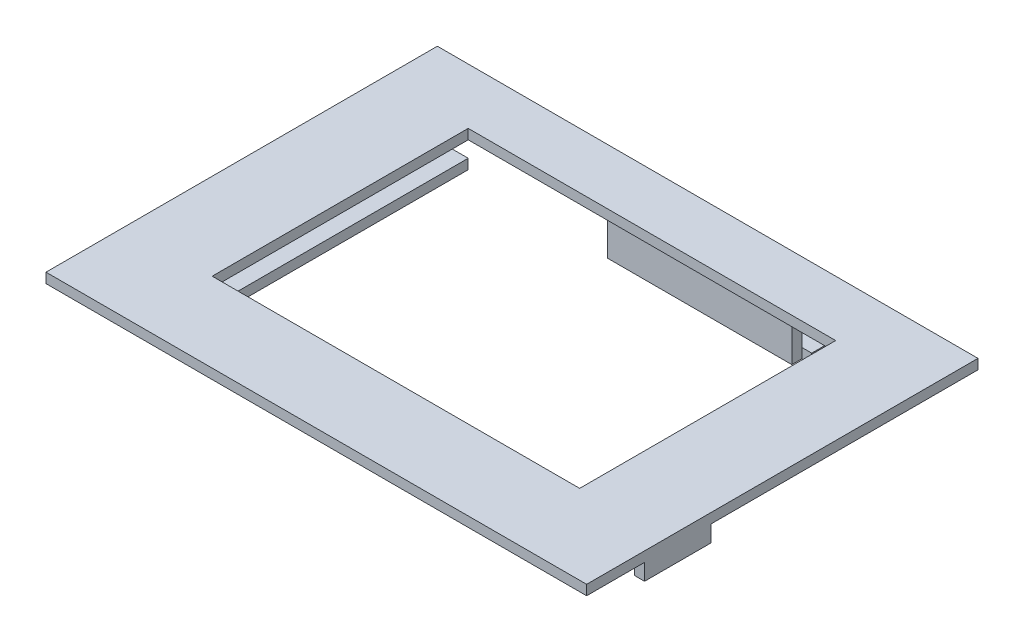
SolidWorks part; units mm, degrees
ref_plane "Front Plane" through (0, 0, 0) normal (0, 0, 1) x (1, 0, 0)
ref_plane "Top Plane" through (0, 0, 0) normal (0, 1, 0) x (1, 0, 0)
ref_plane "Right Plane" through (0, 0, 0) normal (1, 0, 0) x (0, 0, -1)
sketch "Sketch1" plane through (0, 0, 0) normal (0, 1, 0) x (1, 0, 0)
  line L1 (-33.7969, 23.441) -> (20.5331, 23.441)
  line L2 (-33.7969, 23.441) -> (-33.7969, -15.889)
  line L3 (-33.7969, -15.889) -> (20.5331, -15.889)
  line L4 (20.5331, 23.441) -> (20.5331, -15.889)
  dimension "D1" = 39.33
  dimension "D2" = 54.33
extrude "Boss-Extrude1" add sketch "Sketch1" along normal blind 1
sketch "Sketch2" plane through (20.5331, 0, 0) normal (1, 0, 0) x (0, 0, -1)
  line L0 (-15.889, 1) -> (-15.889, 4.0157) construction
  line L1 (-15.889, 4.0157) -> (-10.069, 4.0157) construction
  line L2 (-10.069, 4.0157) -> (-3.369, 4.0157) construction
  line L3 (-15.889, 0) -> (23.441, 0) construction
  line L4 (-10.069, 0) -> (-3.369, 0)
  line L5 (-10.069, 0) -> (-10.069, -1.65)
  line L6 (-10.069, -1.65) -> (-3.369, -1.65)
  line L7 (-3.369, 0) -> (-3.369, -1.65)
  dimension "D1" = 5.82
  dimension "D2" = 6.7
  dimension "D3" = 1.65
extrude "Boss-Extrude2" add sketch "Sketch2" against normal blind 1
sketch "Sketch3" plane through (0, 0, 15.889) normal (0, 0, 1) x (1, 0, 0)
  line L0 (20.5331, 1) -> (20.5331, 7.8741) construction
  line L1 (20.5331, 7.8741) -> (3.8231, 7.8741) construction
  line L2 (-33.7969, 1) -> (-33.7969, 7.8741) construction
  line L3 (-33.7969, 7.8741) -> (-16.6869, 7.8741) construction
  line L4 (-33.7969, 0) -> (20.5331, 0) construction
  line L5 (-16.6869, 0) -> (3.8231, 0)
  line L6 (-16.6869, 0) -> (-16.6869, -4.6)
  line L7 (-16.6869, -4.6) -> (3.8231, -4.6)
  line L8 (3.8231, 0) -> (3.8231, -4.6)
  dimension "D1" = 16.71
  dimension "D2" = 17.11
  dimension "D3" = 4.6
extrude "Boss-Extrude3" add sketch "Sketch3" against normal blind 1
sketch "Sketch5" plane through (0, 1, 0) normal (0, 1, 0) x (1, 0, 0)
  line L0 (-33.7969, 23.441) -> (-31.6756, 21.3197) construction
  line L1 (20.5331, -15.889) -> (18.4118, -13.7677) construction
  line L3 (-31.6756, 21.3197) -> (18.4118, 21.3197)
  line L4 (-31.6756, 21.3197) -> (-31.6756, -13.7677)
  line L5 (-31.6756, -13.7677) -> (18.4118, -13.7677)
  line L6 (18.4118, 21.3197) -> (18.4118, -13.7677)
  dimension "D1" = 3
  dimension "D2" = 3
extrude "Cut-Extrude1" cut sketch "Sketch5" against normal blind 11
sketch "Sketch6" plane through (0, 0, -23.441) normal (0, 0, -1) x (-1, 0, 0)
  line L0 (-20.5331, 1) -> (-20.5331, 5.1933) construction
  line L1 (-20.5331, 5.1933) -> (-2.8231, 5.1933) construction
  line L2 (-2.8231, 5.1933) -> (15.6769, 5.1933) construction
  line L3 (-3.8231, 0) -> (16.6869, 0) construction
  line L4 (-2.8231, 0) -> (15.6769, 0)
  line L5 (-2.8231, 0) -> (-2.8231, -7.9)
  line L6 (-2.8231, -7.9) -> (15.6769, -7.9)
  line L7 (15.6769, 0) -> (15.6769, -7.9)
  dimension "D1" = 17.71
  dimension "D2" = 18.5
  dimension "D3" = 7.9
extrude "Boss-Extrude5" add sketch "Sketch6" against normal blind 1
sketch "Sketch7" plane through (0, -4.6, 0) normal (0, -1, 0) x (1, 0, 0)
  line L1 (-16.6869, 14.889) -> (3.8231, 14.889)
  line L2 (-16.6869, 14.889) -> (-16.6869, 15.889)
  line L3 (-16.6869, 15.889) -> (3.8231, 15.889)
  line L4 (3.8231, 14.889) -> (3.8231, 15.889)
extrude "Cut-Extrude3" cut sketch "Sketch7" against normal blind 4.6
sketch "Sketch10" plane through (-33.7969, 0, 0) normal (-1, 0, 0) x (0, 0, 1)
  line L0 (-23.441, 1) -> (15.889, 1) construction
  line L1 (15.889, 0) -> (7.889, 0)
  line L2 (15.889, 0) -> (15.889, 1)
  line L3 (15.889, 1) -> (7.889, 1)
  line L4 (7.889, 0) -> (7.889, 1)
  line L6 (-23.441, 0) -> (15.889, 0) construction
  line L7 (-23.441, 1) -> (-17.841, 1)
  line L8 (-23.441, 1) -> (-23.441, 0)
  line L9 (-23.441, 0) -> (-17.841, 0)
  line L10 (-17.841, 1) -> (-17.841, 0)
  point P14 (0, 0)
  dimension "D1" = 8
  dimension "D2" = 5.6
extrude "Boss-Extrude8" add sketch "Sketch10" against normal up to vertex (54.33 mm away)
sketch "Sketch11" plane through (0, 0, 15.889) normal (0, 0, 1) x (1, 0, 0)
  line L0 (-33.7969, 1) -> (20.5331, 1) construction
  line L1 (20.5331, 0) -> (11.8331, 0)
  line L2 (20.5331, 0) -> (20.5331, 1)
  line L3 (20.5331, 1) -> (11.8331, 1)
  line L4 (11.8331, 0) -> (11.8331, 1)
  line L5 (-33.7969, 0) -> (20.5331, 0) construction
  line L6 (-33.7969, 1) -> (-25.0969, 1)
  line L7 (-33.7969, 1) -> (-33.7969, 0)
  line L8 (-33.7969, 0) -> (-25.0969, 0)
  line L9 (-25.0969, 1) -> (-25.0969, 0)
  dimension "D1" = 8.7
  dimension "D2" = 8.7
extrude "Boss-Extrude9" add sketch "Sketch11" against normal up to vertex (39.33 mm away)
sketch "Sketch12" plane through (0, 0, -23.441) normal (0, 0, -1) x (-1, 0, 0)
  line L0 (-2.8231, -7.9) -> (-3.8231, -7.9) construction
  line L1 (-3.8231, -7.9) -> (-3.8231, -6.9) construction
  line L3 (-3.8231, -6.9) -> (16.6769, -6.9)
  line L4 (-3.8231, -6.9) -> (-3.8231, -7.9)
  line L5 (-3.8231, -7.9) -> (16.6769, -7.9)
  line L6 (16.6769, -6.9) -> (16.6769, -7.9)
  dimension "D1" = 1
  dimension "D2" = 1
  dimension "D3" = 20.5
extrude "Boss-Extrude10" add sketch "Sketch12" along normal blind 6.25
sketch "Sketch13" plane through (0, 0, 0) normal (0, -1, 0) x (1, 0, 0)
  line L0 (-25.0969, 7.889) -> (-27.0969, 7.889) construction
  line L1 (-25.0969, -17.841) -> (-27.0969, -17.841) construction
  line L2 (11.8331, 7.889) -> (13.8331, 7.889) construction
  line L4 (-29.0969, 7.889) -> (-29.0969, -17.841)
  line L7 (11.8331, -17.841) -> (13.8331, -17.841) construction
  line L12 (15.8331, 7.889) -> (15.8331, -17.841)
  line L13 (15.8331, 7.889) -> (17.8331, 7.889)
  line L14 (15.8331, 7.889) -> (15.8331, -17.841)
  line L15 (15.8331, -17.841) -> (17.8331, -17.841)
  line L16 (17.8331, 7.889) -> (17.8331, -17.841)
  line L17 (-29.0969, -17.841) -> (-31.0969, -17.841)
  line L18 (-29.0969, -17.841) -> (-29.0969, 7.889)
  line L19 (-29.0969, 7.889) -> (-31.0969, 7.889)
  line L20 (-31.0969, -17.841) -> (-31.0969, 7.889)
  dimension "D1" = 4
  dimension "D2" = 4
  dimension "D3" = 2
  dimension "D4" = 2
extrude "Boss-Extrude14" add sketch "Sketch13" along normal blind 2.6 contours L16 L13 L12 L15 | L20 L17 L4 L19
sketch "Sketch16" plane through (15.8331, 0, 0) normal (-1, 0, 0) x (0, 0, 1)
  line L0 (-17.841, -2.6) -> (-17.841, 0) construction
  line L1 (7.889, -2.6) -> (-17.841, -2.6)
  line L2 (7.889, -2.6) -> (7.889, -1.6)
  line L3 (7.889, -1.6) -> (-17.841, -1.6)
  line L4 (-17.841, -2.6) -> (-17.841, -1.6)
  dimension "D1" = 1
extrude "Boss-Extrude15" add sketch "Sketch16" along normal blind 4
sketch "Sketch17" plane through (-29.0969, 0, 0) normal (1, 0, 0) x (0, 0, -1)
  line L0 (17.841, -2.6) -> (17.841, 0) construction
  line L1 (-7.889, -2.6) -> (17.841, -2.6)
  line L2 (-7.889, -2.6) -> (-7.889, -1.6)
  line L3 (-7.889, -1.6) -> (17.841, -1.6)
  line L4 (17.841, -2.6) -> (17.841, -1.6)
  dimension "D1" = 1
extrude "Boss-Extrude16" add sketch "Sketch17" along normal blind 4
